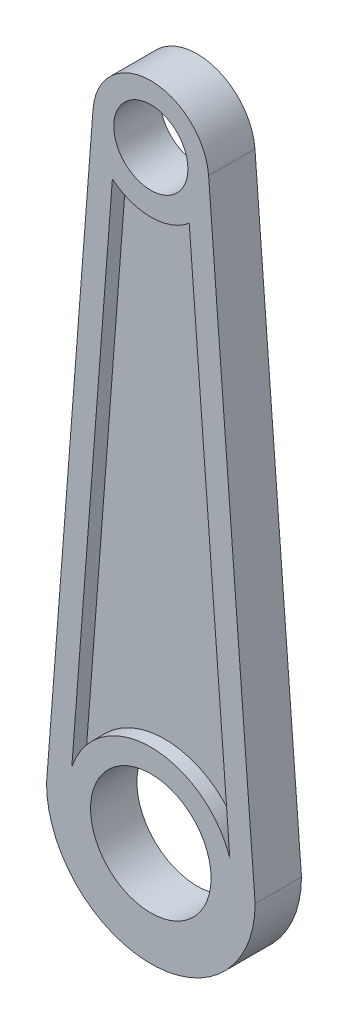
SolidWorks part; units mm, degrees
ref_plane "Front Plane" through (0, 0, 0) normal (0, 0, 1) x (1, 0, 0)
ref_plane "Top Plane" through (0, 0, 0) normal (0, 1, 0) x (1, 0, 0)
ref_plane "Right Plane" through (0, 0, 0) normal (1, 0, 0) x (0, 0, -1)
sketch "Sketch1" plane through (0, 0, 0) normal (0, 0, 1) x (1, 0, 0)
  line L0 (-22.5, 0) -> (-12.4635, 130.9552)
  line L1 (22.5, 0) -> (12.4634, 130.9552)
  circle A0 centre (0, 0) radius 22.5
  circle A1 centre (0, 0) radius 13
  circle A2 centre (0, 130) radius 12.5
  circle A3 centre (0, 130) radius 8
  dimension "D1" = 45
  dimension "D2" = 26
  dimension "D3" = 25
  dimension "D4" = 16
  dimension "D5" = 130
extrude "Boss-Extrude1" add sketch "Sketch1" along normal mid plane 10 contours A2 L0 A0 L1 | A2 A3 | L1 A0 L0 A1
sketch "Sketch2" plane through (0, 0, 5) normal (0, 0, 1) x (1, 0, 0)
  line L4 (17.4991, -0.1793) -> (7.4781, 130.5731)
  line L5 (-7.4781, 130.5731) -> (-17.4991, -0.1793)
  line L6 (17.0411, 5.7967) -> (8.2895, 119.9858)
  line L7 (-8.2895, 119.9858) -> (-17.0411, 5.7967)
  arc A4 (7.4781, 130.5731) -> (-7.4781, 130.5731) centre (0, 130) ccw
  arc A5 (-17.4991, -0.1793) -> (17.4991, -0.1793) centre (0, 0) ccw
  circle A8 centre (0, 130) radius 13
  arc A9 (-8.2895, 119.9858) -> (8.2895, 119.9858) centre (0, 130) ccw
  circle A11 centre (0, 0) radius 18
  arc A12 (17.0411, 5.7967) -> (-17.0411, 5.7967) centre (0, 0) ccw
  dimension "D1" = 5
  dimension "D2" = 5
  dimension "D3" = 5
extrude "Cut-Extrude1" cut sketch "Sketch2" against normal blind 3
mirror "Mirror1" about plane through (0, 0, 0) normal (0, 0, 1) of "Cut-Extrude1"
